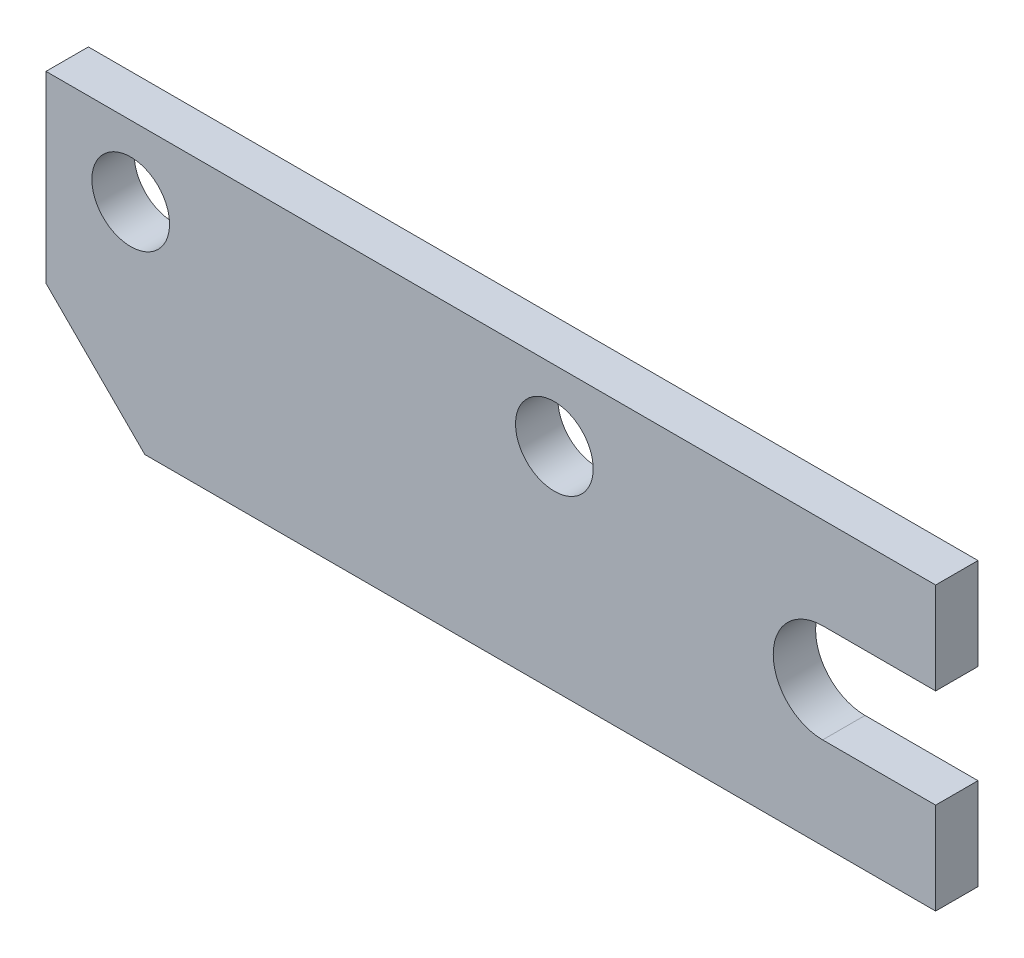
SolidWorks part; units mm, degrees
material "45#"
ref_plane "前视" through (0, 0, 0) normal (0, 0, 1) x (1, 0, 0)
ref_plane "上视" through (0, 0, 0) normal (0, 1, 0) x (1, 0, 0)
ref_plane "右视" through (0, 0, 0) normal (1, 0, 0) x (0, 0, -1)
sketch "草图1" plane through (0, 0, 0) normal (0, 0, 1) x (1, 0, 0)
  line L1 (-31.5, -10) -> (31.5, -10)
  line L2 (-31.5, -10) -> (-31.5, 10)
  line L3 (-31.5, 10) -> (31.5, 10)
  line L4 (31.5, -10) -> (31.5, 10)
  line L5 (-31.5, -10) -> (31.5, 10) construction
  line L6 (-31.5, 10) -> (31.5, -10) construction
  point P0 (0, 0)
  dimension "D1" = 20
  dimension "D2" = 63
extrude "凸台-拉伸1" add sketch "草图1" along normal blind 3
hole_wizard "M5 间隙孔1" positions "草图3" profile "草图2" hole size "M5" standard "Gb" end condition through all
sketch "草图3" plane through (0, 0, 0) normal (0, 0, -1) x (-1, 0, 0)
  line L0 (10.5, 10) -> (10.5, 1.9384) construction
  line L1 (-31.5, 10) -> (31.5, 10) construction
  line L2 (31.5, 10) -> (31.5, -10) construction
  point P0 (25.5, 5)
  point P10 (-4.5, 5)
  dimension "D1" = 30
  dimension "D2" = 21
  dimension "D3" = 5
sketch "草图2" plane through (-25.5, 5, 0) normal (1, 0, 0) x (0, 1, 0)
  line L0 (0, 0) -> (0, 3)
  line L1 (0, 3) -> (2.75, 3)
  line L2 (2.75, 3) -> (2.75, 0)
  line L5 (2.75, 0) -> (0, 0)
  line L11 (0, -6.35) -> (0, 107.95) construction
  dimension "通孔孔直径" = 5.5
  dimension "通孔孔深度" = 3
sketch "草图5" plane through (0, 0, 0) normal (0, 0, -1) x (-1, 0, 0)
  line L0 (-31.5, -10) -> (-31.5, 10) construction
  line L1 (-23.5, 3.5) -> (-31.5, 3.5)
  line L2 (31.5, 10) -> (31.5, -10) construction
  line L3 (-23.5, -3.5) -> (-31.5, -3.5)
  line L4 (-31.5, 3.5) -> (-31.5, -3.5)
  line L5 (-23.5, 3.5) -> (-31.5, -3.5) construction
  line L6 (-23.5, -3.5) -> (-31.5, 3.5) construction
  line L7 (-31.5, 10) -> (31.5, 10) construction
  arc A0 (-23.5, 3.5) -> (-23.5, -3.5) centre (-23.5, 0) cw
  point P0 (-27.5, 0)
  dimension "D1" = 7
  dimension "D2" = 55
  dimension "D3" = 10
extrude "切除-拉伸1" cut sketch "草图5" against normal through all
chamfer "倒角1" distance 7 angle 45 1 edges at (-31.5, -10, 1.5)
